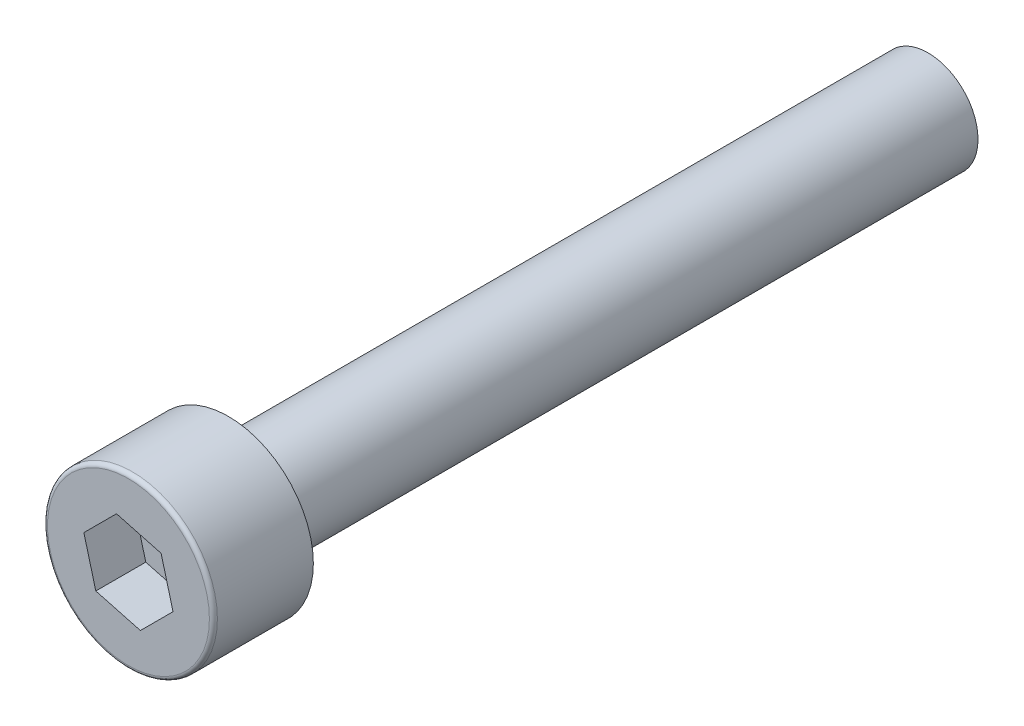
SolidWorks part; units mm, degrees
ref_plane "前视基准面" through (0, 0, 0) normal (0, 0, 1) x (1, 0, 0)
ref_plane "上视基准面" through (0, 0, 0) normal (0, 1, 0) x (1, 0, 0)
ref_plane "右视基准面" through (0, 0, 0) normal (1, 0, 0) x (0, 0, -1)
sketch "草图1" plane through (0, 0, 0) normal (0, 0, 1) x (1, 0, 0)
  circle A0 centre (0, 0) radius 4.25
  dimension "D1" = 8.5
extrude "凸台-拉伸1" add sketch "草图1" along normal blind 5
sketch "草图2" plane through (0, 0, 5) normal (0, 0, 1) x (1, 0, 0)
  line L1 (-1.633, -1.633) -> (0.5977, -2.2307)
  line L2 (0.5977, -2.2307) -> (2.2307, -0.5977)
  line L3 (2.2307, -0.5977) -> (1.633, 1.633)
  line L4 (1.633, 1.633) -> (-0.5977, 2.2307)
  line L5 (-0.5977, 2.2307) -> (-2.2307, 0.5977)
  line L6 (-2.2307, 0.5977) -> (-1.633, -1.633)
  circle A0 centre (0, 0) radius 2 construction
  dimension "D1" = 4
extrude "切除-拉伸1" cut sketch "草图2" against normal blind 2.5
sketch "草图3" plane through (0, 0, 0) normal (0, 0, -1) x (-1, 0, 0)
  circle A0 centre (0, 0) radius 2.5
  dimension "D1" = 5
extrude "凸台-拉伸2" add sketch "草图3" along normal blind 35
fillet "圆角1" radius 0.2 1 edges at (4.25, 0, 5)
